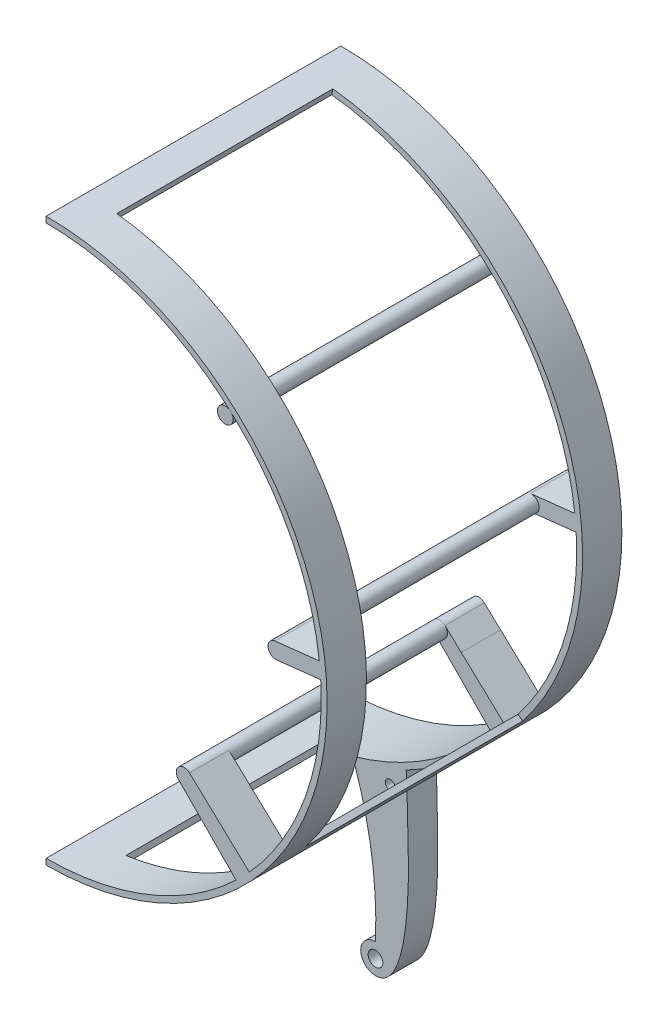
SolidWorks part; units mm, degrees
material "1023 Carbon Steel Sheet (SS)"
ref_plane "Front Plane" through (0, 0, 0) normal (0, 0, 1) x (1, 0, 0)
ref_plane "Top Plane" through (0, 0, 0) normal (0, 1, 0) x (1, 0, 0)
ref_plane "Right Plane" through (0, 0, 0) normal (1, 0, 0) x (0, 0, -1)
ref_plane "Plane1" through (0, 0, -50.1) normal (0, 0, 1) x (1, 0, 0)
sketch "Sketch1" plane through (0, 0, 0) normal (0, 0, 1) x (1, 0, 0)
  line L0 (0, -143) -> (0, -140)
  line L1 (0, 143) -> (0, 140)
  arc A0 (0, -140) -> (0, 140) centre (0, 0) ccw
  arc A1 (0, -143) -> (0, 143) centre (0, 0) ccw
  dimension "D1" = 280
  dimension "D2" = 3
extrude "Boss-Extrude1" add sketch "Sketch1" along normal mid plane 150
sketch "Sketch2" plane through (0, 0, -50.1) normal (0, 0, 1) x (1, 0, 0)
  line L1 (39.3632, -137.4756) -> (65.554, -126.3417)
  circle A0 centre (50, -218.0191) radius 3.75
  arc A1 (50, -210.5177) -> (50, -225.5205) centre (50, -218.0191) ccw
  arc A2 (0, -143) -> (0, 143) centre (0, 0) ccw construction
  circle A8 centre (57.4915, -137.7366) radius 2.5
  spline S0 degree 2 poles (50, -210.5177) (51.5798, -173.0413) (39.3632, -137.4756) knots 0 0 0 1 1 1
  spline S1 degree 3 poles (50, -225.5205) (63.888, -225.5567) (66.6724, -185.5186) (66.8285, -159.2266) (65.8373, -126.4348) (65.554, -126.3417) knots 0 0 0 0 0.384311 0.484311 1 1 1 1
  dimension "D1" = 7.5
extrude "Boss-Extrude2" add sketch "Sketch2" along normal mid plane 15
sketch "Sketch4" plane through (0, 0, 0) normal (0, 0, 1) x (1, 0, 0)
  circle A0 centre (0, 26) radius 114 construction
  arc A1 (0, -140) -> (0, 140) centre (0, 0) ccw construction
  circle A2 centre (91.1621, 100.9231) radius 4
  circle A3 centre (116.9178, 10.0554) radius 4
  circle A4 centre (70.2497, -68.8103) radius 4
  dimension "D1" = 228
  dimension "D2" = 8
  dimension "D3" = 8
  dimension "D4" = 8
extrude "Boss-Extrude3" add sketch "Sketch4" along normal mid plane 150 separate body
sketch "Sketch5" plane through (0, 0, 75) normal (0, 0, 1) x (1, 0, 0)
  line L0 (67.4018, -71.6191) -> (98.3819, -103.03)
  line L1 (72.9832, -65.89) -> (105.049, -95.9057)
  line L2 (98.3819, -103.03) -> (105.049, -95.9057)
  line L3 (116.4789, 14.0312) -> (141.1385, 16.7534)
  line L4 (117.3641, 6.0804) -> (142.2496, 8.8748)
  line L5 (141.1385, 16.7534) -> (142.2496, 8.8748)
  circle A0 centre (70.2497, -68.8103) radius 4 construction
  arc A2 (72.9832, -65.89) -> (67.4018, -71.6191) centre (70.2497, -68.8103) ccw
  circle A3 centre (116.9178, 10.0554) radius 4 construction
  arc A5 (116.4789, 14.0312) -> (117.3641, 6.0804) centre (116.9178, 10.0554) ccw
extrude "Boss-Extrude4" add sketch "Sketch5" against normal blind 20 from surface at 0 starting at face at (70.75, 0, 75)
sketch "Sketch10" plane through (0, 0, -75) normal (0, 0, -1) x (-1, 0, 0)
  line L0 (-81.264, -73.6414) -> (-72.9835, -65.8899)
  line L1 (-72.9832, -65.89) -> (-103.411, -94.3725) construction
  line L2 (-81.264, -73.6414) -> (-103.9095, -94.8391)
  line L3 (-71.7154, -75.9927) -> (-67.4017, -71.6194)
  line L4 (-96.6559, -101.28) -> (-67.4018, -71.6191) construction
  line L5 (-71.7154, -75.9927) -> (-97.325, -101.956)
  line L6 (-97.325, -101.956) -> (-103.9095, -94.8391)
  line L7 (-129.7828, 15.4999) -> (-116.4789, 14.0312)
  line L8 (-116.4789, 14.0312) -> (-139.0219, 16.5198) construction
  line L10 (-139.7361, 8.5925) -> (-117.3641, 6.0804) construction
  line L11 (-131.966, 7.72) -> (-117.3641, 6.0804)
  line L12 (-129.7828, 15.4999) -> (-139.7427, 16.5993)
  line L14 (-131.966, 7.72) -> (-140.6174, 8.675)
  line L15 (-140.6174, 8.675) -> (-139.7427, 16.5993)
  arc A0 (-67.4017, -71.6194) -> (-72.9835, -65.8899) centre (-70.2497, -68.8103) ccw
  arc A1 (-117.3641, 6.0804) -> (-116.4789, 14.0312) centre (-116.9178, 10.0554) ccw
extrude "Boss-Extrude5" add sketch "Sketch10" against normal blind 20
sketch "Sketch14" plane through (0, 0, 0) normal (0, 0, 1) x (1, 0, 0)
  line L5 (110.0513, -86.3712) -> (112.492, -88.2867)
  line L8 (15.3074, 139.0574) -> (15.9424, 142.1085)
  arc A0 (110.0513, -86.3712) -> (139.8909, 1.3435) centre (0, 0) ccw
  arc A1 (112.492, -88.2867) -> (142.9907, 1.6312) centre (0, 0) ccw
  arc A2 (0, -143) -> (0, 143) centre (0, 0) ccw construction
  arc A3 (139.8909, 1.3435) -> (101.5408, 96.2328) centre (0, 0) ccw
  arc A4 (142.9907, 1.6312) -> (103.4681, 98.7084) centre (0, 0) ccw
  arc A5 (101.5408, 96.2328) -> (15.3074, 139.0574) centre (0, 0) ccw
  arc A6 (103.4681, 98.7084) -> (15.9424, 142.1085) centre (0, 0) ccw
extrude "Cut-Extrude1" cut sketch "Sketch14" against normal up to surface and the other way up to surface up to face at (66.2497, -68.8103, -55) other way up to face at (85.8584, -84.0167, 55)
sketch "Sketch15" plane through (0, 0, 0) normal (0, 0, 1) x (1, 0, 0)
  line L0 (86.5353, -110.0529) -> (88.3896, -112.4112)
  line L1 (20.5584, -138.4823) -> (20.9989, -141.4498)
  arc A0 (20.5584, -138.4823) -> (86.5353, -110.0529) centre (0, 0) ccw
  arc A1 (20.9989, -141.4498) -> (88.3896, -112.4112) centre (0, 0) ccw
extrude "Cut-Extrude2" cut sketch "Sketch15" against normal up to surface (97.6 mm away) from surface at -42.6
sketch "Sketch16" plane through (0, 0, 0) normal (0, 0, 1) x (1, 0, 0)
  line L2 (83.8476, -112.1142) -> (85.6443, -114.5166)
  line L3 (23.1038, -138.0805) -> (23.5989, -141.0393)
  line L4 (0, 0) -> (83.8476, -112.1142) construction
  arc A0 (0, -143) -> (0, 143) centre (0, 0) ccw construction
  arc A4 (23.5989, -141.0393) -> (85.6443, -114.5166) centre (0, 0) ccw
  arc A5 (23.1038, -138.0805) -> (83.8476, -112.1142) centre (0, 0) ccw
  arc A6 (0, -140) -> (96.6559, -101.28) centre (0, 0) ccw construction
sketch "Sketch17" plane through (0, 0, 0) normal (0, 1, 0) x (1, 0, 0)
  line L0 (0, 95.4142) -> (0, -96.7896)
  line L4 (0, 100.5718) -> (0, 95.4142)
  line L5 (0, 100.5718) -> (-176.7312, 100.5718)
  line L6 (-176.7312, 100.5718) -> (-176.7312, -96.7896)
  line L7 (-176.7312, -96.7896) -> (0, -96.7896)
